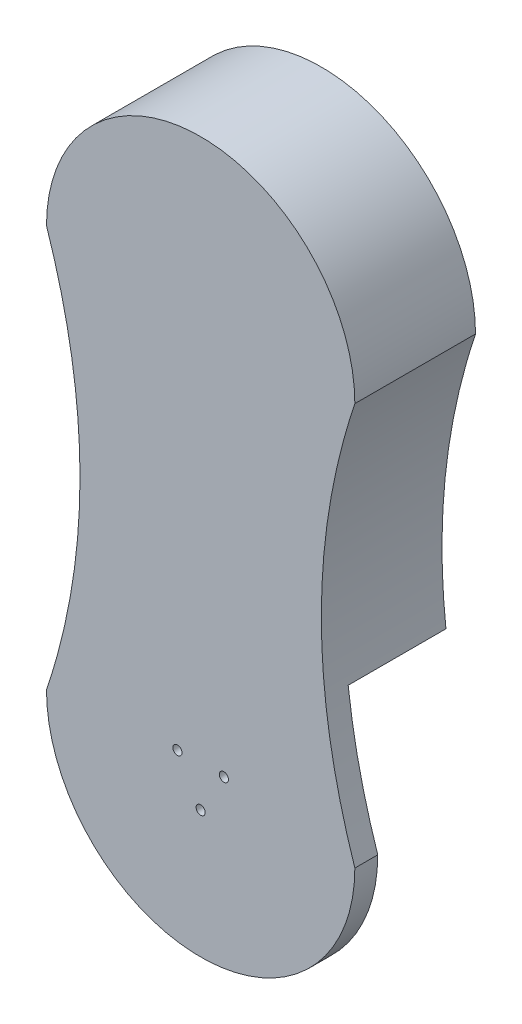
SolidWorks part; units mm, degrees
ref_plane "Front Plane" through (0, 0, 0) normal (1, 0, 0) x (0, 1, 0)
ref_plane "Top Plane" through (0, 0, 0) normal (0, 0, 1) x (0, 1, 0)
ref_plane "Right Plane" through (0, 0, 0) normal (0, 1, 0) x (-1, 0, 0)
sketch "Sketch1" plane through (0, 0, 0) normal (0, 0, 1) x (0, 1, 0)
  line L0 (0, 0) -> (300, 0) construction
  arc A0 (0, 115) -> (0, -115) centre (0, 0) ccw
  arc A1 (300, -115) -> (300, 115) centre (300, 0) ccw
  spline S0 degree 2 poles (0, 115) (150, 65) (300, 115) knots 0 0 0 1 1 1
  spline S1 degree 2 poles (0, -115) (150, -65) (300, -115) knots 0 0 0 1 1 1
  point P12 (150, 0)
  dimension "D1" = 230
  dimension "D2" = 300
  dimension "D3" = 180
extrude "Boss-Extrude1" add sketch "Sketch1" along normal blind 90
sketch "Sketch2" plane through (0, 0, 0) normal (0, 0, -1) x (1, 0, 0)
  circle A0 centre (0, 0) radius 97.5
  dimension "D1" = 195
extrude "Cut-Extrude1" cut sketch "Sketch2" against normal blind 72.91
sketch "Sketch10" plane through (0, 0, 0) normal (0, 0, -1) x (1, 0, 0)
  arc A1 (115, 0) -> (-115, 0) centre (0, 0) ccw construction
  arc A2 (115, 0) -> (-115, 0) centre (0, 0) ccw
  arc A3 (-92.9457, -98.5109) -> (92.9457, -98.5109) centre (0, 72.36) ccw
  parabola Q0 (-115, -300) -> (-115, 0) focus (-315, -150) apex (-90, -150) construction
  parabola Q1 (-92.9457, -98.5109) -> (-115, 0) focus (-315, -150) apex (-90, -150)
  parabola Q2 (115, 0) -> (115, -300) focus (315, -150) apex (90, -150) construction
  parabola Q3 (115, 0) -> (92.9457, -98.5109) focus (315, -150) apex (90, -150)
  parabola Q4 (-115, -300) -> (-115, 0) focus (-315, -150) apex (-90, -150) construction
extrude "Cut-Extrude10" cut sketch "Sketch10" against normal up to surface (72.91 mm away) up to face at (-97.5, 0, 72.91)
sketch "Sketch13" plane through (0, 0, 72.91) normal (0, 0, -1) x (1, 0, 0)
  line L0 (0, 0) -> (0, 20) construction
  line L1 (0, 0) -> (-17.3205, -10) construction
  line L2 (0, 0) -> (17.3205, -10) construction
  circle A3 centre (0, 20) radius 3.4
  circle A4 centre (-17.3205, -10) radius 3.4
  circle A5 centre (17.3205, -10) radius 3.4
  dimension "D2" = 20
  dimension "D4" = 120
  dimension "D1" = 6.8
  dimension "D3" = 120
extrude "Cut-Extrude13" cut sketch "Sketch13" against normal up to surface (17.09 mm away) up to face at (0, 150, 90)
